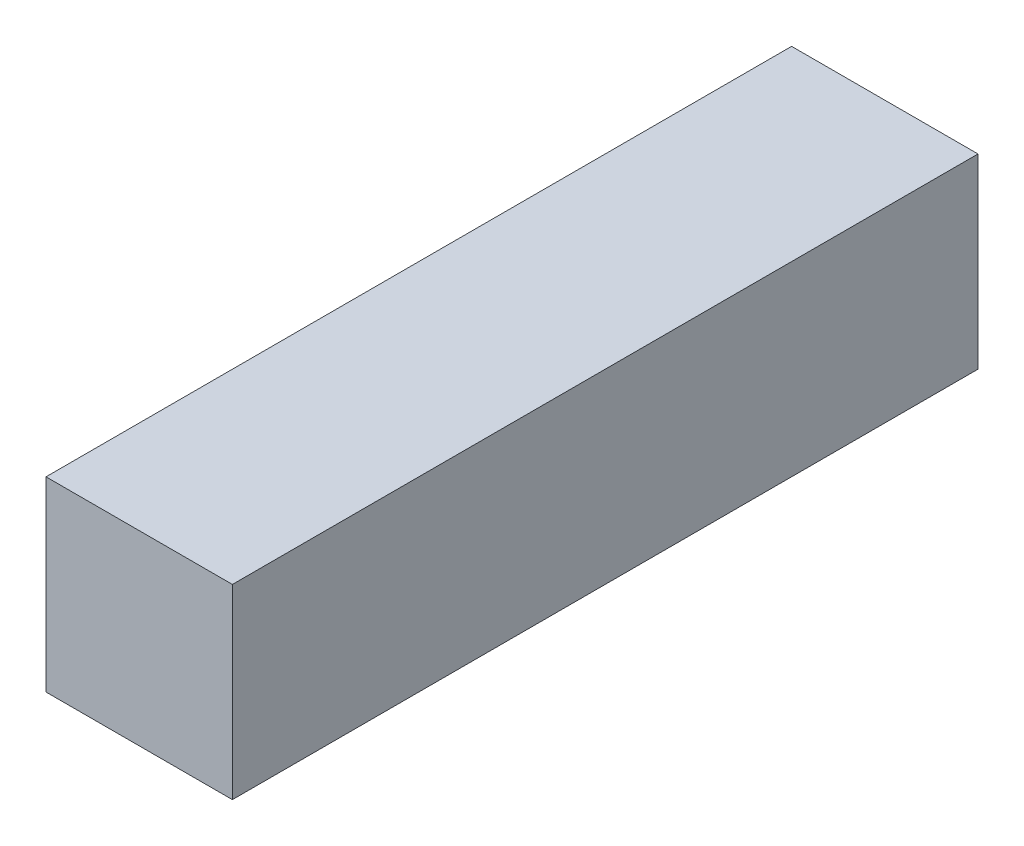
SolidWorks part; units mm, degrees
ref_plane "Alzado" through (0, 0, 0) normal (0, 0, 1) x (1, 0, 0)
ref_plane "Planta" through (0, 0, 0) normal (0, 1, 0) x (1, 0, 0)
ref_plane "Vista lateral" through (0, 0, 0) normal (1, 0, 0) x (0, 0, -1)
sketch "Croquis1" plane through (0, 0, 0) normal (0, 0, 1) x (1, 0, 0)
  line L1 (2.5, -2.5) -> (-2.5, -2.5)
  line L2 (2.5, -2.5) -> (2.5, 2.5)
  line L3 (2.5, 2.5) -> (-2.5, 2.5)
  line L4 (-2.5, -2.5) -> (-2.5, 2.5)
  line L5 (2.5, -2.5) -> (-2.5, 2.5) construction
  line L6 (2.5, 2.5) -> (-2.5, -2.5) construction
  point P0 (0, 0)
  dimension "D1" = 5
  dimension "D2" = 5
extrude "Saliente-Extruir1" add sketch "Croquis1" along normal blind 20
